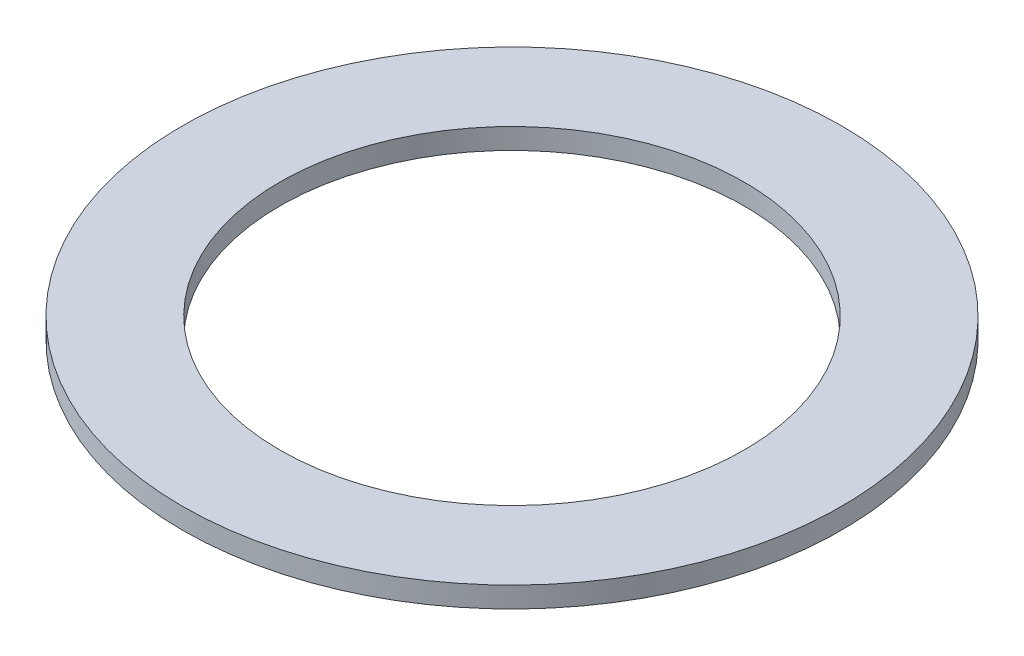
SolidWorks part; units mm, degrees
ref_plane "Ebene vorne" through (0, 0, 0) normal (0, 0, 1) x (1, 0, 0)
ref_plane "Ebene oben" through (0, 0, 0) normal (0, 1, 0) x (1, 0, 0)
ref_plane "Ebene rechts" through (0, 0, 0) normal (1, 0, 0) x (0, 0, -1)
sketch "Skizze1" plane through (0, 0, 0) normal (0, 1, 0) x (1, 0, 0)
  circle A0 centre (0, 0) radius 7.95
  circle A1 centre (0, 0) radius 5.6
  dimension "D1" = 15.9
  dimension "D2" = 11.2
extrude "Aufsatz-Linear austragen1" add sketch "Skizze1" along normal blind 0.5
